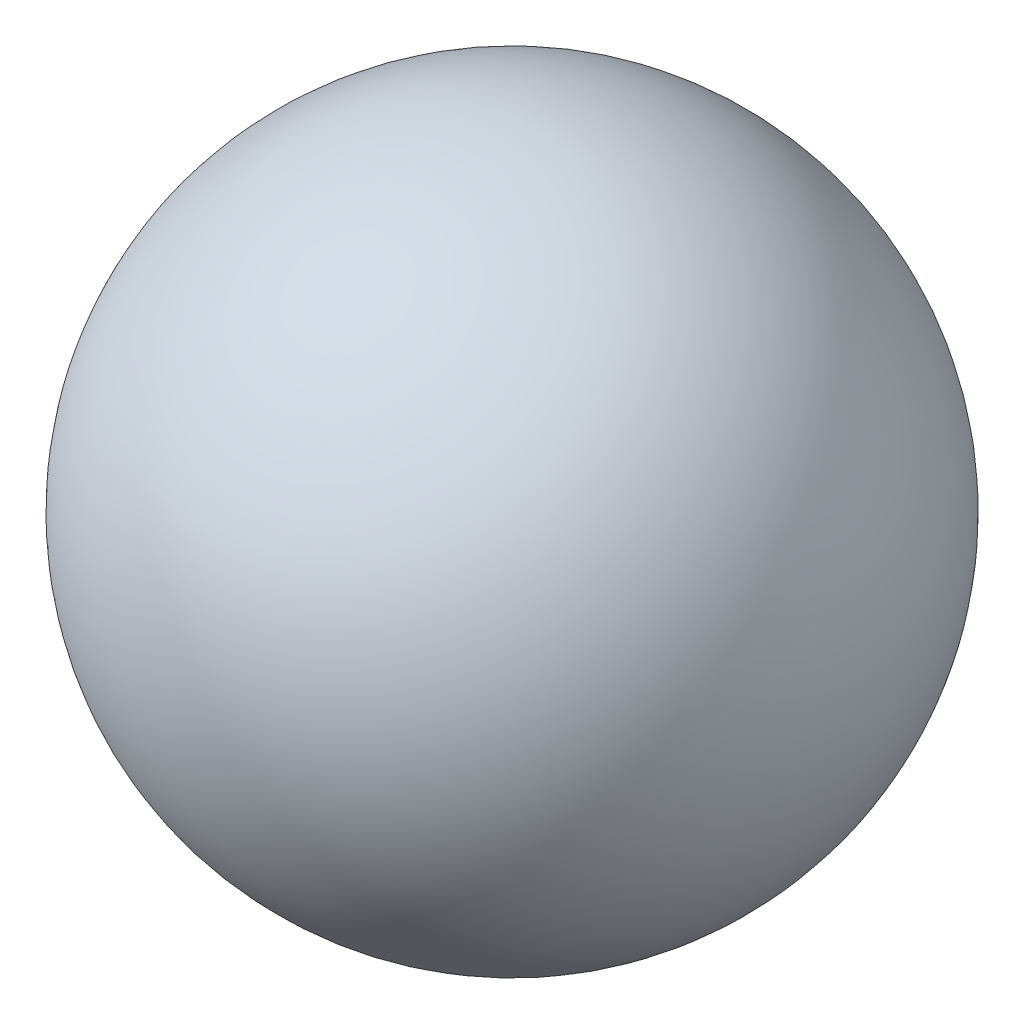
SolidWorks part; units mm, degrees
ref_plane "Front Plane" through (0, 0, 0) normal (0, 0, 1) x (1, 0, 0)
ref_plane "Top Plane" through (0, 0, 0) normal (0, 1, 0) x (1, 0, 0)
ref_plane "Right Plane" through (0, 0, 0) normal (1, 0, 0) x (0, 0, -1)
sketch "Sketch1" plane through (0, 0, 0) normal (0, 0, 1) x (1, 0, 0)
  line L0 (0, 0) -> (-208.4205, 0) construction
  line L1 (-38.1, 0) -> (38.1, 0)
  arc A0 (38.1, 0) -> (-38.1, 0) centre (0, 0) ccw
  dimension "D1" = 38.1
revolve "Revolve1" add sketch "Sketch1" angle 360 about L0
